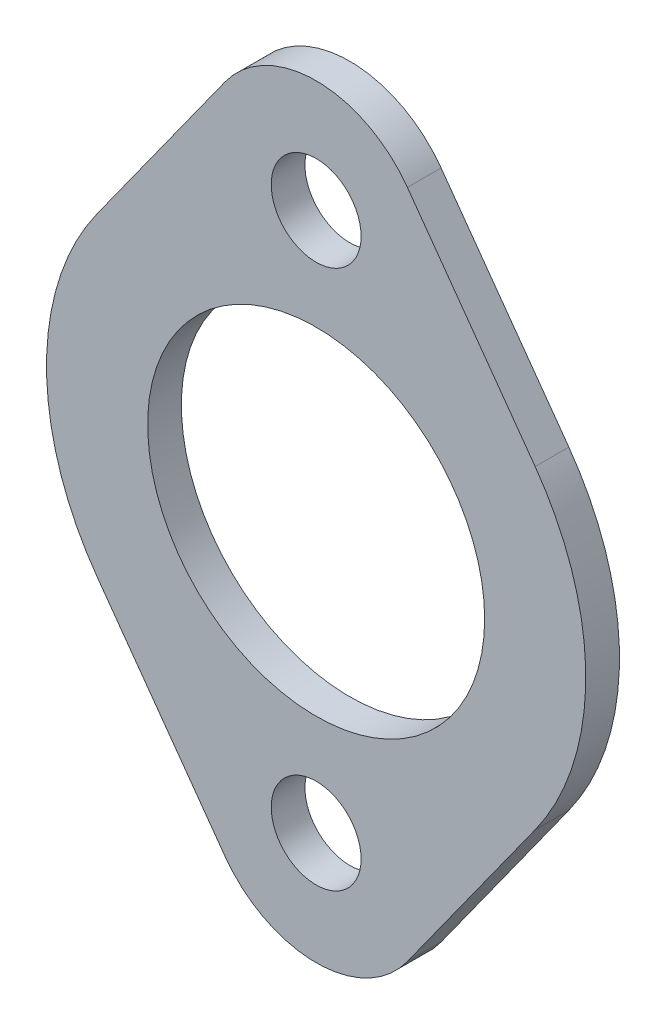
SolidWorks part; units mm, degrees
material "PW20:29:Sc:0:"
ref_plane "Front" through (0, 0, 0) normal (0, 0, 1) x (1, 0, 0)
ref_plane "Top" through (0, 0, 0) normal (0, 1, 0) x (1, 0, 0)
ref_plane "Right" through (0, 0, 0) normal (1, 0, 0) x (0, 0, -1)
sketch "Sketch1" plane through (0, 0, 0) normal (0, 0, 1) x (1, 0, 0)
  line L0 (0, 0) -> (0, 94.4945) construction
  line L1 (0, 0) -> (88.837, 0) construction
  line L2 (12.8942, 47.3604) -> (30.9461, 22.225)
  line L3 (12.8942, -47.3604) -> (30.9461, -22.225)
  line L4 (-12.8942, 47.3604) -> (-30.9461, 22.225)
  line L5 (-12.8942, -47.3604) -> (-30.9461, -22.225)
  arc A0 (-12.8942, 47.3604) -> (12.8942, 47.3604) centre (0, 38.1) cw
  arc A1 (-12.8942, -47.3604) -> (12.8942, -47.3604) centre (0, -38.1) ccw
  arc A2 (30.9461, 22.225) -> (30.9461, -22.225) centre (0, 0) cw
  arc A3 (-30.9461, -22.225) -> (-30.9461, 22.225) centre (0, 0) cw
  dimension "EndR" = 15.875
  dimension "SideR" = 38.1
  dimension "CtoC" = 76.2
extrude "Main" add sketch "Sketch1" along normal blind 4.7625
sketch "Sketch2" plane through (0, 0, 4.7625) normal (0, 0, 1) x (1, 0, 0)
  circle A0 centre (0, 38.1) radius 6.35
  circle A1 centre (0, -38.1) radius 6.35
  circle A2 centre (0, 0) radius 23.8125
  dimension "BoltH" = 12.7
  dimension "CenterH" = 47.625
extrude "Holes" cut sketch "Sketch2" against normal through all
